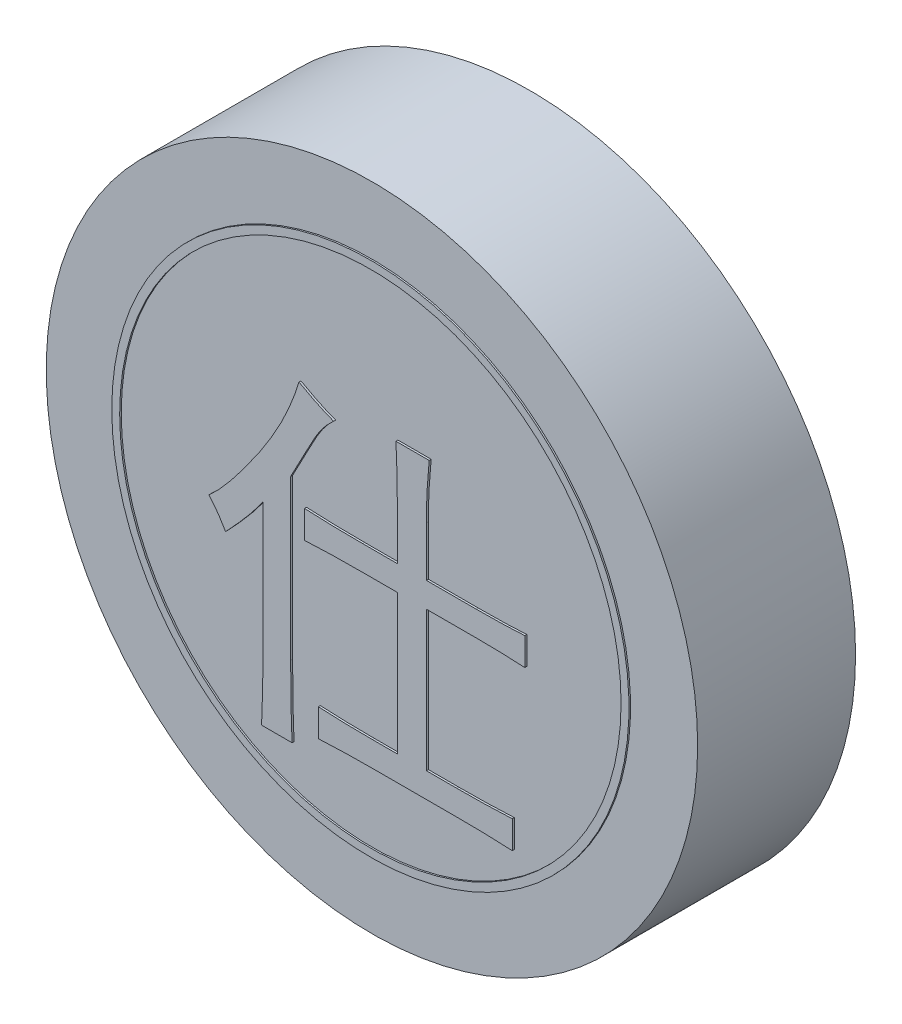
SolidWorks part; units mm, degrees
ref_plane "前视基准面" through (0, 0, 0) normal (0, 0, 1) x (1, 0, 0)
ref_plane "上视基准面" through (0, 0, 0) normal (0, 1, 0) x (1, 0, 0)
ref_plane "右视基准面" through (0, 0, 0) normal (1, 0, 0) x (0, 0, -1)
other "Configuration Table"
sketch "草图1" plane through (0, 0, 0) normal (0, 0, 1) x (1, 0, 0)
  circle A0 centre (0, 0) radius 16.5
  dimension "D1" = 33
extrude "Diameter33_Height8" add sketch "草图1" against normal blind 8
sketch "草图2" plane through (0, 0, 0) normal (0, 0, 1) x (1, 0, 0)
  text T0 "仕" font "SimHei" height 12
extrude "Character_仕" add sketch "草图2" along normal blind 0.1
sketch "草图3" plane through (0, 0, 0) normal (0, 0, 1) x (1, 0, 0)
  circle A0 centre (0, 0) radius 13.1
  circle A1 centre (0, 0) radius 12.7
extrude "Ink_ring" add sketch "草图3" along normal blind 0.08
